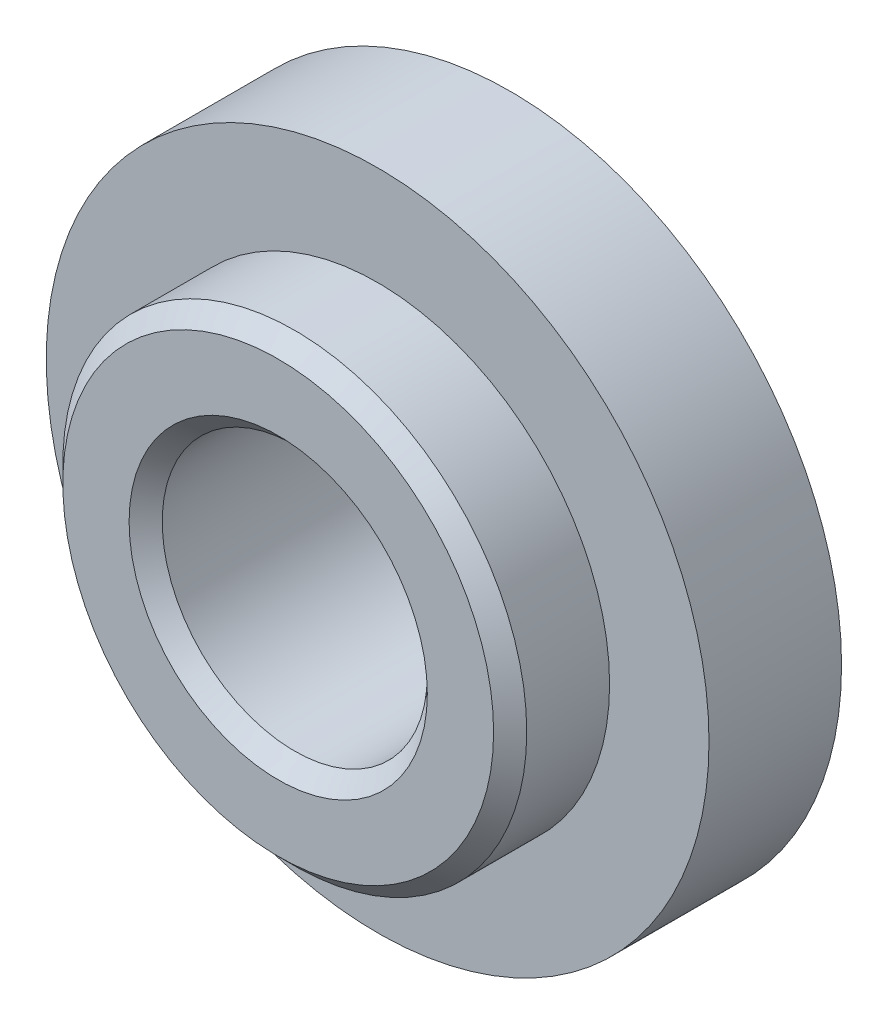
SolidWorks part; units mm, degrees
ref_plane "Plan1" through (0, 0, 0) normal (0, 0, 1) x (1, 0, 0)
ref_plane "Plan2" through (0, 0, 0) normal (0, 1, 0) x (1, 0, 0)
ref_plane "Plan3" through (0, 0, 0) normal (1, 0, 0) x (0, 0, -1)
sketch "Esquisse1" plane through (0, 0, 0) normal (0, 0, 1) x (1, 0, 0)
  circle A0 centre (0, 0) radius 10
  circle A1 centre (0, 0) radius 4
  dimension "D1" = 20
  dimension "D2" = 8
extrude "Base-Extrusion" add sketch "Esquisse1" along normal blind 4
sketch "Esquisse2" plane through (0, 0, 4) normal (0, 0, 1) x (1, 0, 0)
  circle A0 centre (0, 0) radius 7
  circle A1 centre (0, 0) radius 4
  dimension "D1" = 14
  dimension "D2" = 8
extrude "Boss.-Extru.1" add sketch "Esquisse2" along normal blind 3
chamfer "Chanfrein3" distance 0.5 angle 45
